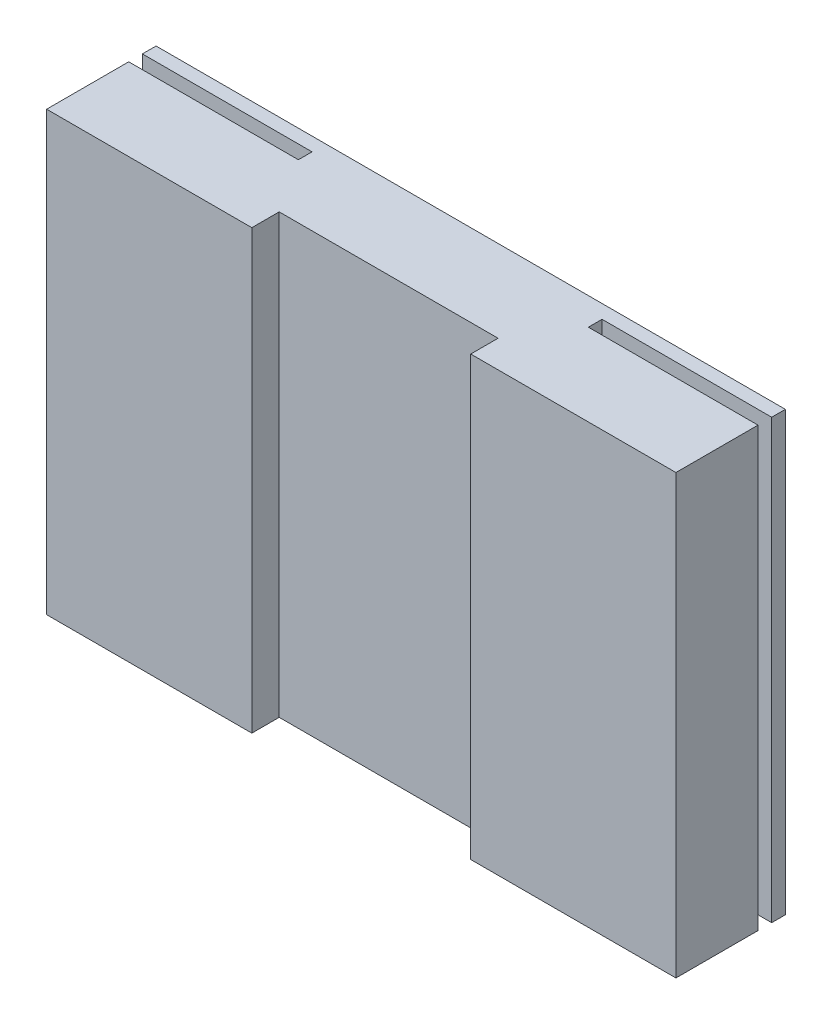
SolidWorks part; units mm, degrees
ref_plane "Front Plane" through (0, 0, 0) normal (0, 0, 1) x (1, 0, 0)
ref_plane "Top Plane" through (0, 0, 0) normal (0, 1, 0) x (1, 0, 0)
ref_plane "Right Plane" through (0, 0, 0) normal (1, 0, 0) x (0, 0, -1)
sketch "Sketch1" plane through (0, 0, 0) normal (0, 1, 0) x (1, 0, 0)
  line L1 (18.2562, -2.3812) -> (-18.2563, -2.3813)
  line L2 (18.2562, -2.3812) -> (18.2562, 2.3813)
  line L3 (18.2562, 2.3813) -> (-18.2563, 2.3812)
  line L4 (-18.2563, -2.3813) -> (-18.2563, 2.3812)
  line L5 (18.2562, -2.3812) -> (-18.2563, 2.3812) construction
  line L6 (18.2562, 2.3813) -> (-18.2563, -2.3813) construction
  point P0 (0, 0)
  dimension "D1" = 4.7625
  dimension "D2" = 36.5125
extrude "Boss-Extrude1" add sketch "Sketch1" along normal blind 25.4
sketch "Sketch2" plane through (0, 25.4, 0) normal (0, 1, 0) x (1, 0, 0)
  line L0 (-6.35, -2.3813) -> (6.35, -2.3813)
  line L1 (-18.2563, -2.3813) -> (18.2562, -2.3812) construction
  line L2 (-6.35, -2.3813) -> (-6.35, -0.7938)
  line L3 (-6.35, -0.7938) -> (6.35, -0.7938)
  line L4 (6.35, -0.7938) -> (6.35, -2.3813)
  dimension "D3" = 1.5875
extrude "Cut-Extrude1" cut sketch "Sketch2" against normal blind 25.4
sketch "Sketch3" plane through (0, 0, -2.3813) normal (0, 0, -1) x (-1, 0, 0)
  line L1 (-18.2562, 0) -> (18.2563, 0) construction
  line L2 (-8.4137, 25.4) -> (8.4138, 25.4)
  line L3 (-8.4137, 25.4) -> (-8.4137, 0)
  line L4 (-8.4137, 0) -> (8.4138, 0)
  line L5 (8.4138, 25.4) -> (8.4138, 0)
  line L6 (-8.4137, 25.4) -> (8.4138, 0) construction
  line L10 (-8.4137, 0) -> (8.4138, 25.4) construction
  line L11 (18.2563, 25.4) -> (18.2563, 0) construction
  line L12 (-18.2562, 25.4) -> (-18.2562, 0) construction
  point P0 (0, 12.7)
  point P1 (0, 12.7)
  dimension "D1" = 9.8425
  dimension "D2" = 9.8425
extrude "Boss-Extrude2" add sketch "Sketch3" along normal blind 0.7937
sketch "Sketch4" plane through (0, 0, -3.175) normal (0, 0, -1) x (-1, 0, 0)
  line L0 (-18.2562, 0) -> (-8.4137, 0) construction
  line L1 (18.2563, 25.4) -> (-18.2562, 25.4)
  line L2 (18.2563, 25.4) -> (18.2563, 0)
  line L3 (18.2563, 0) -> (-18.2562, 0)
  line L4 (-18.2562, 25.4) -> (-18.2562, 0)
  line L5 (18.2563, 25.4) -> (-18.2562, 0) construction
  line L6 (18.2563, 0) -> (-18.2562, 25.4) construction
  line L7 (-18.2562, 25.4) -> (-8.4137, 25.4) construction
  line L8 (-18.2562, 25.4) -> (-18.2562, 0) construction
  line L9 (18.2563, 25.4) -> (18.2563, 0) construction
  point P0 (0, 12.7)
  dimension "D1" = 0
  dimension "D2" = 0
  dimension "D3" = 0
  dimension "D4" = 0
extrude "Boss-Extrude3" add sketch "Sketch4" along normal blind 0.7937
